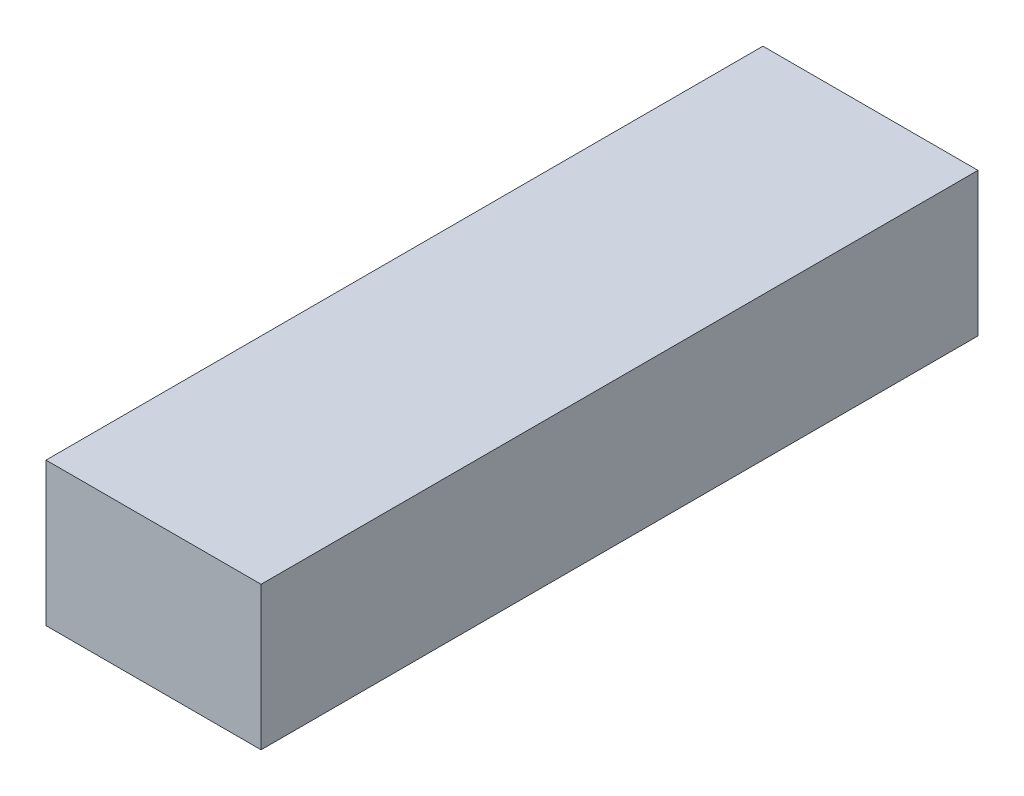
SolidWorks part; units mm, degrees
ref_plane "Front Plane" through (0, 0, 0) normal (0, 0, 1) x (1, 0, 0)
ref_plane "Top Plane" through (0, 0, 0) normal (0, 1, 0) x (1, 0, 0)
ref_plane "Right Plane" through (0, 0, 0) normal (1, 0, 0) x (0, 0, -1)
sketch "Sketch1" plane through (0, 0, 0) normal (0, 0, 1) x (1, 0, 0)
  line L1 (-3, -2) -> (3, -2)
  line L2 (-3, -2) -> (-3, 2)
  line L3 (-3, 2) -> (3, 2)
  line L4 (3, -2) -> (3, 2)
  line L5 (-3, -2) -> (3, 2) construction
  line L6 (-3, 2) -> (3, -2) construction
  point P0 (0, 0)
  dimension "D1" = 6
  dimension "D2" = 4
extrude "Boss-Extrude1" add sketch "Sketch1" against normal blind 20
